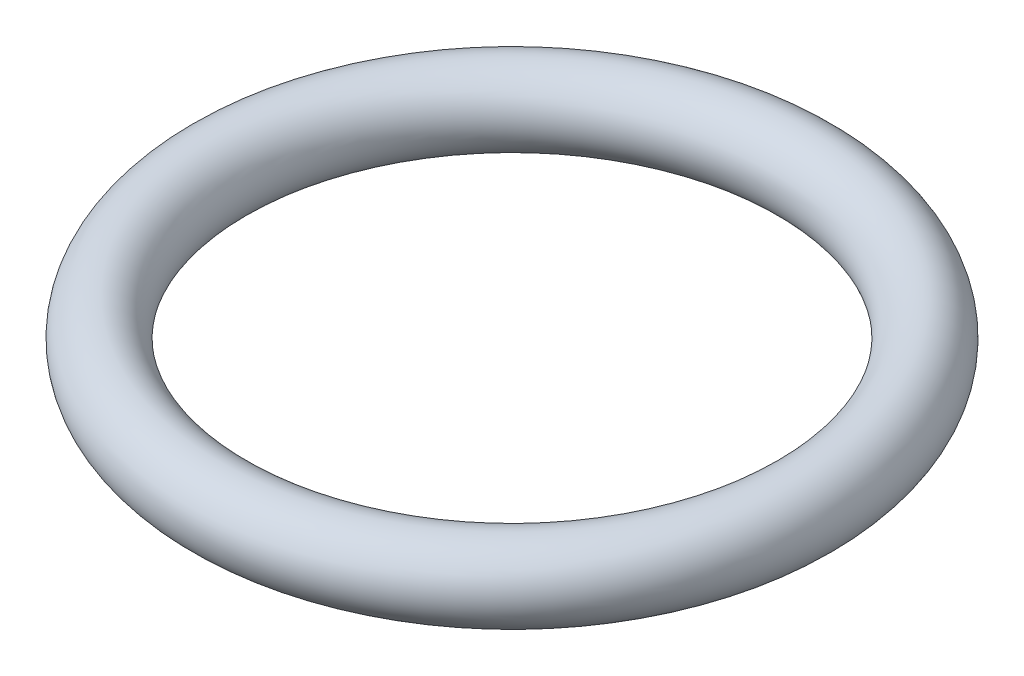
SolidWorks part; units mm, degrees
material "VITON"
ref_plane "Front Plane" through (0, 0, 0) normal (0, 0, 1) x (1, 0, 0)
ref_plane "Top Plane" through (0, 0, 0) normal (0, 1, 0) x (1, 0, 0)
ref_plane "Right Plane" through (0, 0, 0) normal (1, 0, 0) x (0, 0, -1)
sketch "MainBodyS" plane through (0, 0, 0) normal (0, 0, 1) x (1, 0, 0)
  line L0 (0, 0) -> (5.45, 0) construction
  line L1 (0, 0) -> (0, -1) construction
  circle A0 centre (5.45, 0) radius 0.7
  point P3 (6.15, 0)
  point P6 (-6.15, 0)
  point P7 (-4.75, 0)
  point P8 (4.75, 0)
  dimension "Dia" = 1.4
  dimension "RefRevolve" = 1
  dimension "RevolveDia" = 10.9
  dimension "OD" = 12.3
  dimension "ID" = 9.5
revolve "MAIN BODY" add sketch "MainBodyS" angle 360 about L1
